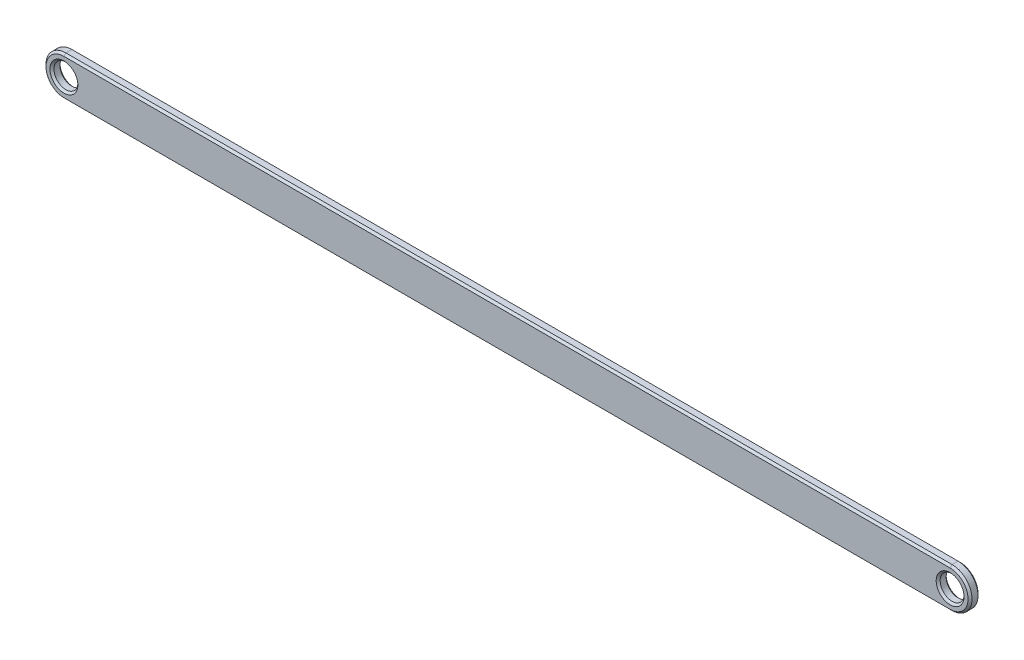
SolidWorks part; units mm, degrees
ref_plane "Front Plane" through (0, 0, 0) normal (0, 0, 1) x (1, 0, 0)
ref_plane "Top Plane" through (0, 0, 0) normal (0, 1, 0) x (1, 0, 0)
ref_plane "Right Plane" through (0, 0, 0) normal (1, 0, 0) x (0, 0, -1)
sketch "Sketch1" plane through (0, 0, 0) normal (0, 0, 1) x (1, 0, 0)
  line L0 (0, 157.4916) -> (0, -223.2358) construction
  line L1 (1112.5, -50) -> (-1112.5, -50)
  line L3 (1112.5, 50) -> (-1112.5, 50)
  line L4 (-1112.5, 0) -> (1112.5, 0) construction
  arc A0 (-1112.5, 50) -> (-1112.5, -50) centre (-1112.5, 0) ccw
  circle A1 centre (-1112.5, 0) radius 30
  arc A2 (1112.5, 50) -> (1112.5, -50) centre (1112.5, 0) cw
  circle A3 centre (1112.5, 0) radius 30
  point P0 (0, 0)
  dimension "D1" = 60
  dimension "D2" = 20
  dimension "D3" = 2225
extrude "Boss-Extrude1" add sketch "Sketch1" along normal blind 25
chamfer "Chamfer1" distance 5 angle 45 12 edges at (1082.5, 0, 0) (-1082.5, 0, 0) (0, -50, 0) (1162.5, 0, 0) (0, 50, 0) (-1162.5, 0, 0) (1082.5, 0, 25) (0, 50, 25) (1162.5, 0, 25) (0, -50, 25) (-1162.5, 0, 25) (-1082.5, 0, 25)
equation "\"length\" = 2225"
equation "\"D3@Sketch1\"=\"length\""
